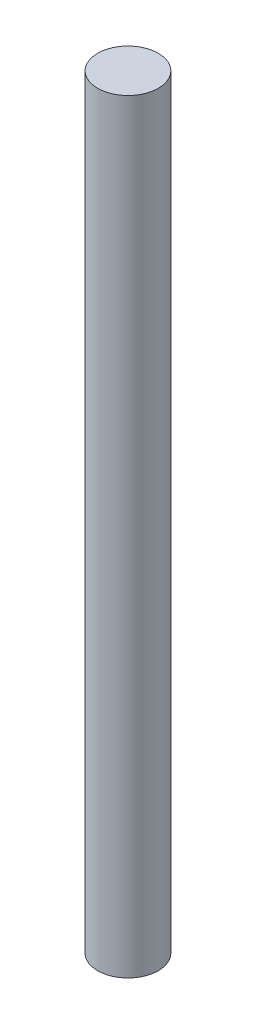
SolidWorks part; units mm, degrees
ref_plane "Front Plane" through (0, 0, 0) normal (0, 0, 1) x (1, 0, 0)
ref_plane "Top Plane" through (0, 0, 0) normal (0, 1, 0) x (1, 0, 0)
ref_plane "Right Plane" through (0, 0, 0) normal (1, 0, 0) x (0, 0, -1)
sketch "Sketch1" plane through (0, 0, 0) normal (0, 1, 0) x (1, 0, 0)
  circle A0 centre (0, 0) radius 3.175
  dimension "D1" = 6.35
extrude "Boss-Extrude1" add sketch "Sketch1" along normal blind 80
